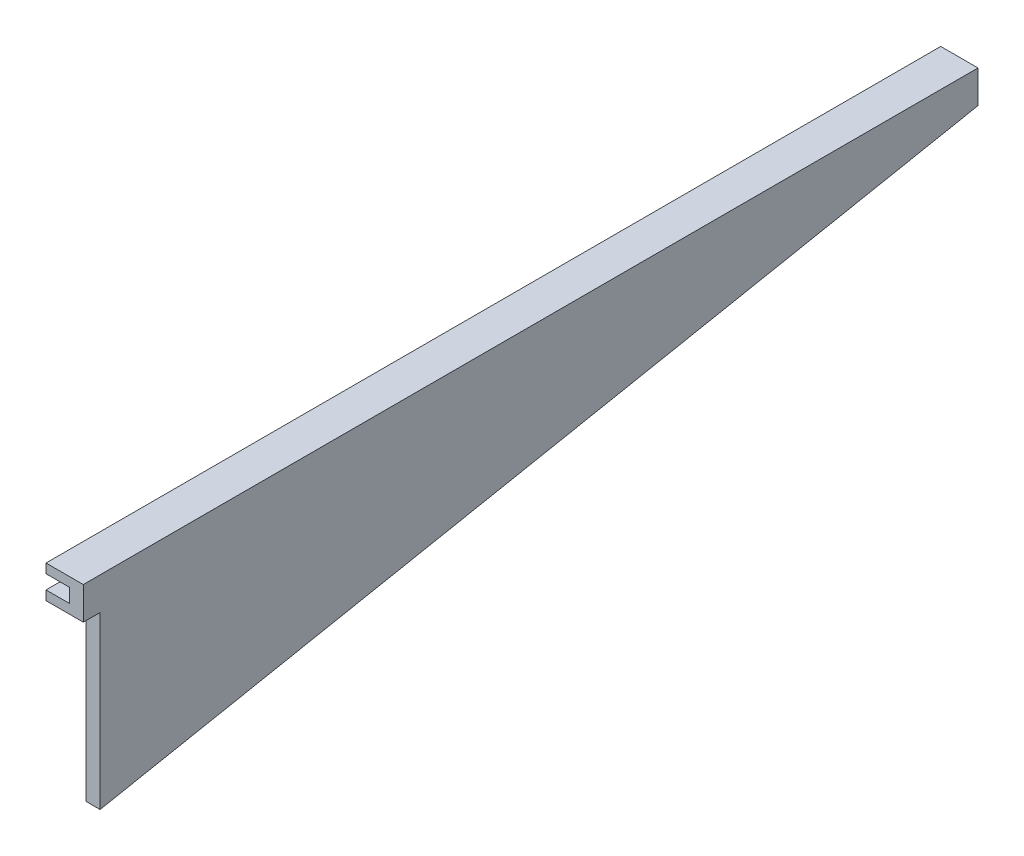
SolidWorks part; units mm, degrees
ref_plane "Front Plane" through (0, 0, 0) normal (0, 0, 1) x (1, 0, 0)
ref_plane "Top Plane" through (0, 0, 0) normal (0, 1, 0) x (1, 0, 0)
ref_plane "Right Plane" through (0, 0, 0) normal (1, 0, 0) x (0, 0, -1)
sketch "Sketch1" plane through (0, 0, 0) normal (0, 0, 1) x (1, 0, 0)
  line L1 (4, -3.5) -> (-4, -3.5)
  line L2 (4, -3.5) -> (4, 3.5)
  line L3 (4, 3.5) -> (-4, 3.5)
  line L4 (-4, -3.5) -> (-4, 3.5)
  line L5 (4, -3.5) -> (-4, 3.5) construction
  line L6 (4, 3.5) -> (-4, -3.5) construction
  point P0 (0, 0)
  dimension "D1" = 8
  dimension "D2" = 7
extrude "Boss-Extrude1" add sketch "Sketch1" along normal blind 192
sketch "Sketch2" plane through (0, 0, 192) normal (0, 0, 1) x (1, 0, 0)
  line L0 (-4, 3.5) -> (-4, -3.5) construction
  line L1 (-4, 1.5) -> (1, 1.5)
  line L2 (-4, 1.5) -> (-4, -1.5)
  line L3 (-4, -1.5) -> (1, -1.5)
  line L4 (1, 1.5) -> (1, -1.5)
  dimension "D1" = 3
  dimension "D2" = 5
extrude "Cut-Extrude1" cut sketch "Sketch2" against normal blind 192
sketch "Sketch3" plane through (4, 0, 0) normal (1, 0, 0) x (0, 0, -1)
  line L0 (0, -3.5) -> (-188.4013, -40.1215)
  line L1 (-188.4013, -40.1215) -> (-188.4013, -3.5)
  line L2 (-192, -3.5) -> (0, -3.5) construction
  line L7 (0, -3.5) -> (0, 3.5)
  line L8 (0, 3.5) -> (-192, 3.5)
  line L9 (-192, 3.5) -> (-192, -3.5)
  line L10 (-192, -3.5) -> (0, -3.5)
  line L11 (0, -3.5) -> (0, 3.5)
  line L12 (0, 3.5) -> (-192, 3.5)
  line L13 (-192, 3.5) -> (-192, -3.5)
  line L14 (-192, -3.5) -> (-188.4013, -3.5)
  dimension "D1" = 11
  dimension "D2" = 0
extrude "Boss-Extrude2" add sketch "Sketch3" along normal blind 0.001 and the other way blind 3
